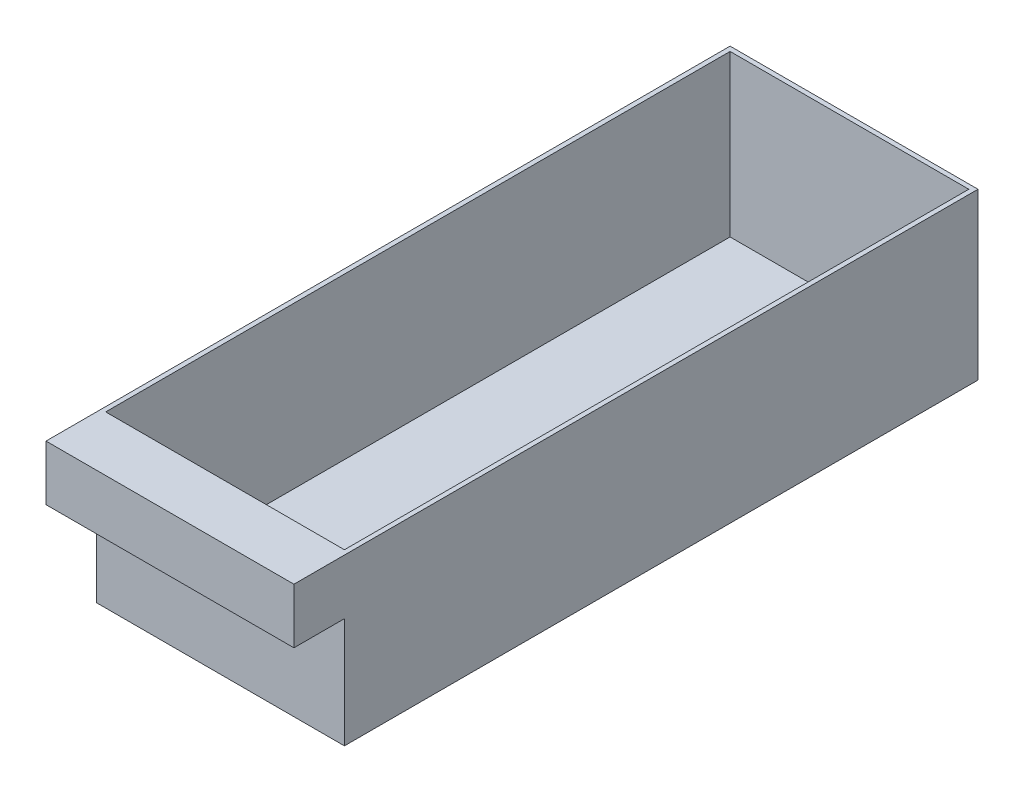
SolidWorks part; units mm, degrees
ref_plane "前视基准面" through (0, 0, 0) normal (0, 0, 1) x (1, 0, 0)
ref_plane "上视基准面" through (0, 0, 0) normal (0, 1, 0) x (1, 0, 0)
ref_plane "右视基准面" through (0, 0, 0) normal (1, 0, 0) x (0, 0, -1)
other "Configuration Table"
sketch "草图4" plane through (0, 0, 0) normal (0, 1, 0) x (1, 0, 0)
  line L6 (-27, -69) -> (27, -69)
  line L11 (-27, -69) -> (-27, 69)
  line L12 (-27, 69) -> (27, 69)
  line L13 (27, -69) -> (27, 69)
  line L14 (-27, -69) -> (27, 69) construction
  line L15 (-27, 69) -> (27, -69) construction
  point P0 (0, 0)
  dimension "D1" = 54
  dimension "D2" = 138
extrude "凸台-拉伸1" add sketch "草图4" along normal blind 36
shell "抽壳1" thickness 1
sketch "草图5" plane through (0, 0, 69) normal (0, 0, 1) x (1, 0, 0)
  line L0 (27, 36) -> (27, 0) construction
  line L1 (-27, 36) -> (27, 36)
  line L2 (-27, 36) -> (-27, 24)
  line L3 (-27, 24) -> (27, 24)
  line L4 (27, 36) -> (27, 24)
  dimension "D1" = 12
extrude "凸台-拉伸2" add sketch "草图5" along normal blind 11
sketch "草图6" plane through (0, 24, 0) normal (0, -1, 0) x (1, 0, 0)
  line L0 (-27, 80) -> (27, 80) construction
  line L1 (-26, 79) -> (26, 79)
  line L2 (-26, 79) -> (-26, 69)
  line L3 (-26, 69) -> (26, 69)
  line L4 (26, 79) -> (26, 69)
  line L5 (27, 80) -> (27, 69) construction
  line L6 (-27, 80) -> (-27, 69) construction
  line L9 (-27, 69) -> (27, 69) construction
  dimension "D1" = 1
  dimension "D2" = 1
  dimension "D3" = 1
extrude "切除-拉伸1" cut sketch "草图6" against normal offset from surface (11 mm away) 1 up to face at (0, 36, 5.5)
